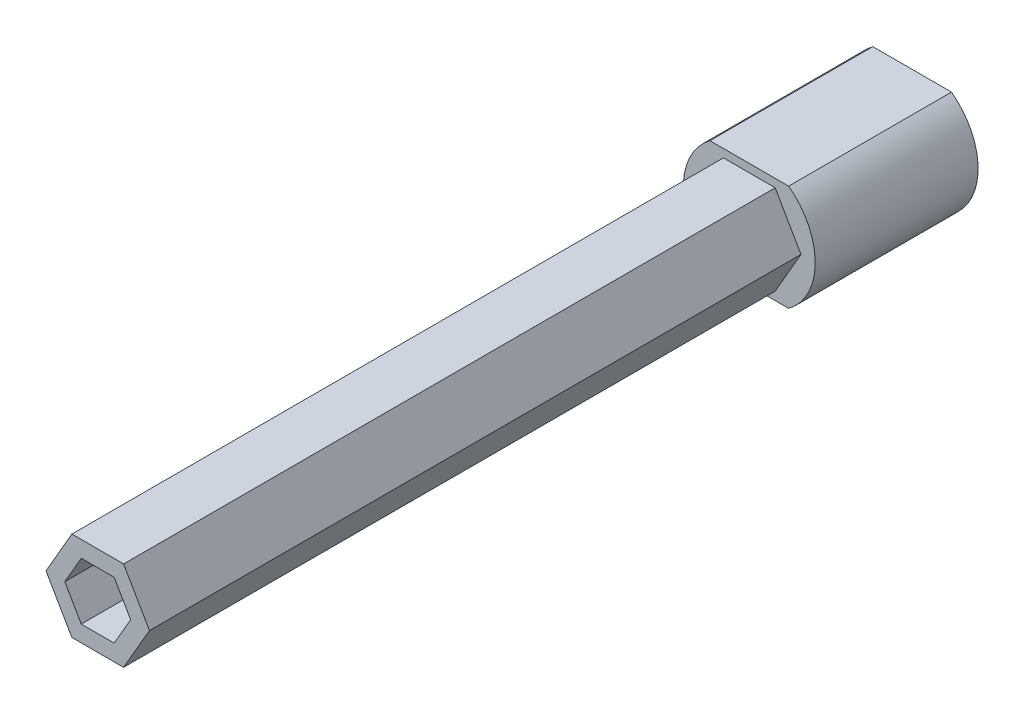
SolidWorks part; units mm, degrees
ref_plane "Front Plane" through (0, 0, 0) normal (0, 0, 1) x (1, 0, 0)
ref_plane "Top Plane" through (0, 0, 0) normal (0, 1, 0) x (1, 0, 0)
ref_plane "Right Plane" through (0, 0, 0) normal (1, 0, 0) x (0, 0, -1)
sketch "Sketch1" plane through (0, 0, 0) normal (0, 0, 1) x (1, 0, 0)
  line L0 (-2.4166, 3.25) -> (2.4166, 3.25)
  line L1 (-2.4166, -3.25) -> (2.4166, -3.25)
  arc A0 (-2.4166, 3.25) -> (-2.4166, -3.25) centre (0, 0) ccw
  arc A2 (2.4166, -3.25) -> (2.4166, 3.25) centre (0, 0) ccw
  dimension "D1" = 8.1
  dimension "D3" = 6.5
extrude "Boss-Extrude2" add sketch "Sketch1" along normal blind 10
sketch "Sketch3" plane through (0, 0, 0) normal (0, 0, -1) x (-1, 0, 0)
  line L0 (2.0591, 2.25) -> (-2.0591, 2.25)
  line L1 (-2.0591, -2.25) -> (2.0591, -2.25)
  line L2 (2.4166, 3.25) -> (-2.4166, 3.25)
  line L3 (-2.4166, -3.25) -> (2.4166, -3.25)
  line L4 (2.4166, 3.25) -> (-2.4166, 3.25)
  line L5 (-2.4166, -3.25) -> (2.4166, -3.25)
  arc A0 (2.0591, -2.25) -> (2.0591, 2.25) centre (0, 0) ccw
  arc A1 (-2.0591, 2.25) -> (-2.0591, -2.25) centre (0, 0) ccw
  arc A2 (2.4166, -3.25) -> (2.4166, 3.25) centre (0, 0) ccw
  arc A3 (-2.4166, 3.25) -> (-2.4166, -3.25) centre (0, 0) ccw
  arc A4 (2.4166, -3.25) -> (2.4166, 3.25) centre (0, 0) ccw
  arc A5 (-2.4166, 3.25) -> (-2.4166, -3.25) centre (0, 0) ccw
  dimension "D1" = 0
  dimension "D2" = 1
extrude "Cut-Extrude2" cut sketch "Sketch3" against normal blind 8 contours A0 L0 A1 L1
sketch "Sketch4" plane through (0, 0, 10) normal (0, 0, 1) x (1, 0, 0)
  line L1 (1.5861, -2.751) -> (3.1754, -0.0019)
  line L2 (3.1754, -0.0019) -> (1.5894, 2.749)
  line L3 (1.5894, 2.749) -> (-1.5861, 2.751)
  line L4 (-1.5861, 2.751) -> (-3.1754, 0.0019)
  line L5 (-3.1754, 0.0019) -> (-1.5894, -2.749)
  line L6 (-1.5894, -2.749) -> (1.5861, -2.751)
  circle A0 centre (0, 0) radius 2.75 construction
  dimension "D1" = 5.5
extrude "Boss-Extrude3" add sketch "Sketch4" along normal blind 40
sketch "Sketch5" plane through (0, 0, 50) normal (0, 0, 1) x (1, 0, 0)
  line L12 (-1.0114, -1.7494) -> (1.0093, -1.7506)
  line L13 (1.0093, -1.7506) -> (2.0207, -0.0012)
  line L14 (2.0207, -0.0012) -> (1.0114, 1.7494)
  line L15 (1.0114, 1.7494) -> (-1.0093, 1.7506)
  line L16 (-1.0093, 1.7506) -> (-2.0207, 0.0012)
  line L17 (-2.0207, 0.0012) -> (-1.0114, -1.7494)
  line L18 (-1.0114, -1.7494) -> (1.0093, -1.7506)
  line L19 (1.0093, -1.7506) -> (2.0207, -0.0012)
  line L20 (2.0207, -0.0012) -> (1.0114, 1.7494)
  line L21 (1.0114, 1.7494) -> (-1.0093, 1.7506)
  line L22 (-1.0093, 1.7506) -> (-2.0207, 0.0012)
  line L23 (-2.0207, 0.0012) -> (-1.0114, -1.7494)
  dimension "D1" = 1
extrude "Cut-Extrude3" cut sketch "Sketch5" against normal through all both and the other way through all
